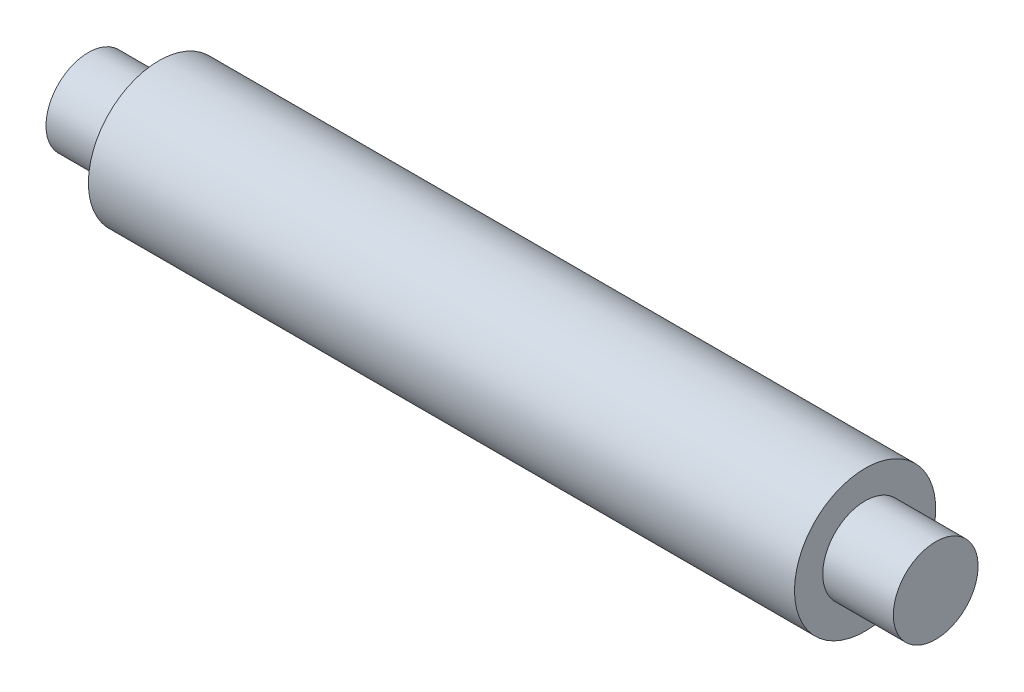
SolidWorks part; units mm, degrees
ref_plane "前基準面" through (0, 0, 0) normal (0, 0, 1) x (1, 0, 0)
ref_plane "上基準面" through (0, 0, 0) normal (0, 1, 0) x (1, 0, 0)
ref_plane "右基準面" through (0, 0, 0) normal (1, 0, 0) x (0, 0, -1)
ref_plane "平面1"
sketch "草圖1" plane through (0, 0, 0) normal (0, 0, 1) x (1, 0, 0)
  line L0 (110, 0) -> (120, 0)
  line L1 (120, 0) -> (120, 6)
  line L2 (120, 6) -> (110, 6)
  line L3 (110, 6) -> (110, 0)
  line L4 (10, 0) -> (110, 0) construction
  line L5 (0, 0) -> (10, 0)
  line L6 (10, 0) -> (10, 6)
  line L7 (10, 6) -> (0, 6)
  line L8 (0, 6) -> (0, 0)
  line L9 (10, 0) -> (110, 0)
  line L10 (110, 0) -> (110, 10)
  line L11 (110, 10) -> (10, 10)
  line L12 (10, 10) -> (10, 0)
  dimension "D1" = 10
  dimension "D2" = 6
  dimension "D3" = 100
  dimension "D4" = 10
  dimension "D5" = 10
  dimension "D6" = 6
revolve "迴轉1" add sketch "草圖1" angle 360 about L4
